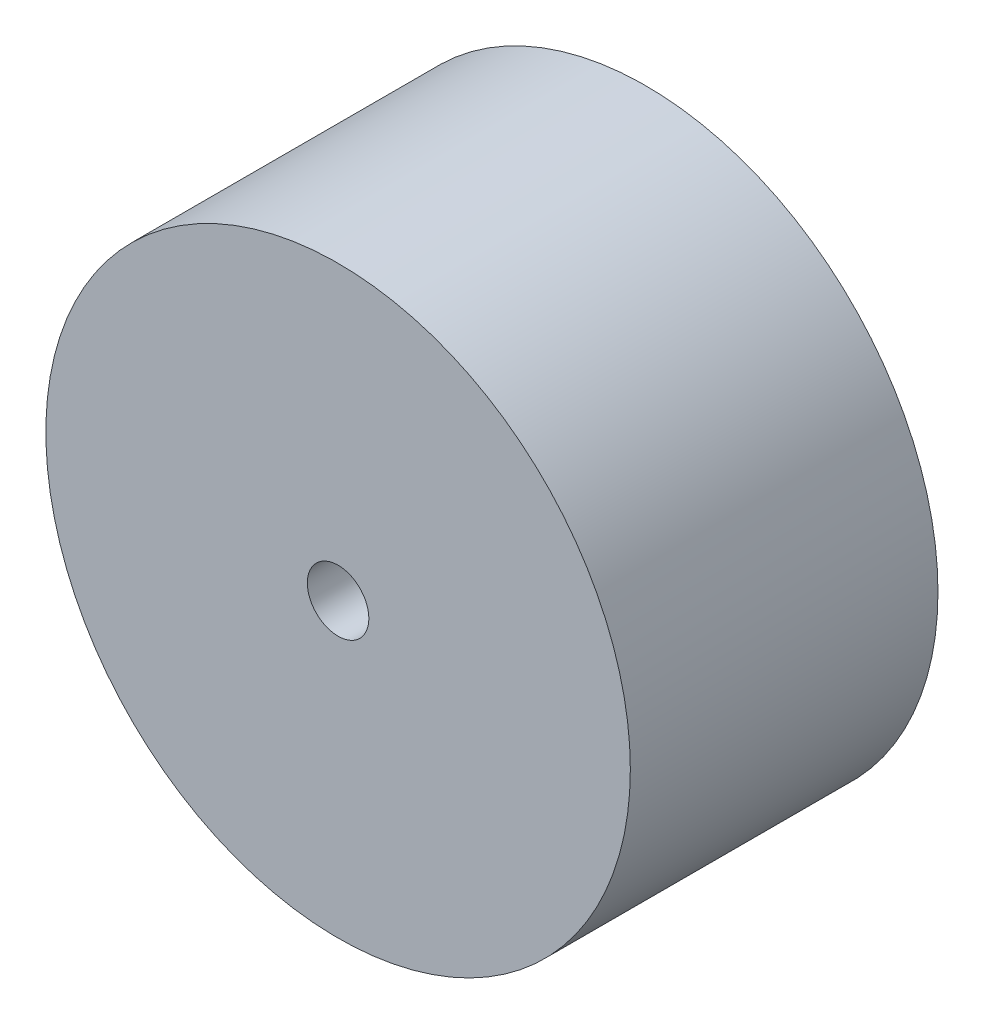
SolidWorks part; units mm, degrees
ref_plane "Front Plane" through (0, 0, 0) normal (0, 0, 1) x (1, 0, 0)
ref_plane "Top Plane" through (0, 0, 0) normal (0, 1, 0) x (1, 0, 0)
ref_plane "Right Plane" through (0, 0, 0) normal (1, 0, 0) x (0, 0, -1)
sketch "Sketch1" plane through (0, 0, 0) normal (0, 0, 1) x (1, 0, 0)
  circle A0 centre (0, 0) radius 19
  dimension "D1" = 38
extrude "Boss-Extrude1" add sketch "Sketch1" along normal blind 20
sketch "Sketch2" plane through (0, 0, 20) normal (0, 0, 1) x (1, 0, 0)
  circle A0 centre (0, 0) radius 2
extrude "Cut-Extrude1" cut sketch "Sketch2" against normal through all
